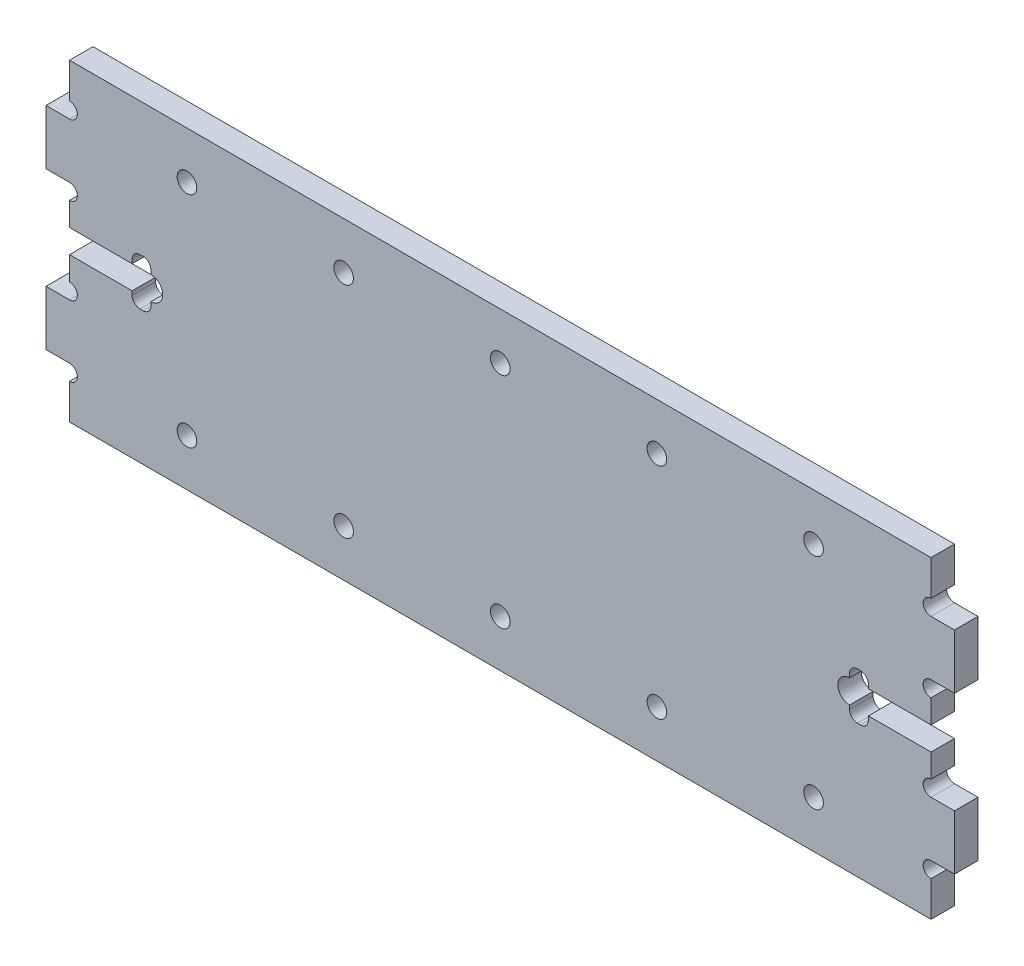
SolidWorks part; units mm, degrees
material "Acrylic (Medium-high impact)"
ref_plane "Front Plane" through (0, 0, 0) normal (0, 0, 1) x (1, 0, 0)
ref_plane "Top Plane" through (0, 0, 0) normal (0, 1, 0) x (1, 0, 0)
ref_plane "Right Plane" through (0, 0, 0) normal (1, 0, 0) x (0, 0, -1)
sketch "Sketch1" plane through (0, 0, 0) normal (0, 0, 1) x (1, 0, 0)
  line L0 (0, 20) -> (0, -20) construction
  line L1 (-55, 20) -> (55, 20)
  line L2 (-55, 20) -> (-55, -20)
  line L3 (-55, -20) -> (55, -20)
  line L4 (55, 20) -> (55, -20)
  line L5 (55, 0) -> (-55, 0) construction
  point P8 (0, 0)
extrude "Boss-Extrude1" add sketch "Sketch1" along normal blind 3
sketch "Sketch2" plane through (0, 0, 3) normal (0, 0, 1) x (1, 0, 0)
  line L0 (-55, 0) -> (55, 0) construction
  line L1 (-55, 20) -> (-55, -20) construction
  line L2 (55, -20) -> (55, 20) construction
  line L3 (55, 0) -> (55, -20) construction
  line L4 (55, 0) -> (55, 20) construction
  line L5 (55, 20) -> (58, 20) construction
  line L6 (58, 20) -> (58, -20) construction
  line L7 (58, -20) -> (55, -20) construction
  line L8 (0, 20) -> (0, -20) construction
  line L9 (55, 20) -> (-55, 20) construction
  line L10 (-55, -20) -> (55, -20) construction
  line L11 (55, -10) -> (58, -10) construction
  line L12 (55, 10) -> (58, 10) construction
  line L13 (58, 10) -> (58, 13.5)
  line L14 (58, 10) -> (58, 6.5)
  line L15 (58, 6.5) -> (55, 6.5)
  line L16 (55, 6.5) -> (55, 13.5)
  line L17 (55, 13.5) -> (58, 13.5)
  line L18 (55, -10) -> (55, -6.5)
  line L19 (55, -6.5) -> (58, -6.5)
  line L20 (58, -6.5) -> (58, -13.5)
  line L21 (58, -13.5) -> (55, -13.5)
  line L22 (55, -13.5) -> (55, -10)
  line L23 (-55, 6.5) -> (-55, 13.5)
  line L24 (-55, -13.5) -> (-55, -10)
  line L25 (-55, -10) -> (-55, -6.5)
  line L26 (-55, 10) -> (-58, 10) construction
  line L27 (-55, -10) -> (-58, -10) construction
  line L28 (-58, -20) -> (-55, -20) construction
  line L29 (-58, 20) -> (-58, -20) construction
  line L30 (-55, 20) -> (-58, 20) construction
  line L31 (-58, -13.5) -> (-55, -13.5)
  line L32 (-58, -6.5) -> (-58, -13.5)
  line L33 (-55, -6.5) -> (-58, -6.5)
  line L34 (-55, 13.5) -> (-58, 13.5)
  line L35 (-58, 6.5) -> (-55, 6.5)
  line L36 (-58, 10) -> (-58, 6.5)
  line L37 (-58, 10) -> (-58, 13.5)
extrude "Boss-Extrude2" add sketch "Sketch2" against normal blind 3
sketch "Sketch3" plane through (0, 0, 3) normal (0, 0, 1) x (1, 0, 0)
  line L0 (-55, 0) -> (55, 0) construction
  line L1 (-55, 6.5) -> (-55, -6.5) construction
  line L2 (55, -6.5) -> (55, 6.5) construction
  line L3 (-55, 13.5) -> (-55, 14.5) construction
  line L4 (-55, 20) -> (-55, 13.5) construction
  line L5 (-55, 14.5) -> (55, 14.5) construction
  line L6 (55, 13.5) -> (55, 20) construction
  line L7 (55, 14.5) -> (55, 5.5) construction
  line L8 (55, 5.5) -> (-55, 5.5) construction
  line L9 (-55, -6.5) -> (-55, -5.5) construction
  line L10 (-55, -5.5) -> (55, -5.5) construction
  line L11 (55, -5.5) -> (55, -14.5) construction
  line L12 (55, -20) -> (55, -13.5) construction
  line L13 (55, -14.5) -> (-55, -14.5) construction
  line L14 (-55, -13.5) -> (-55, -20) construction
  circle A1 centre (-55, 14.5) radius 1
  circle A2 centre (-55, 5.5) radius 1
  circle A3 centre (-55, -5.5) radius 1
  circle A4 centre (-55, -14.5) radius 1
  circle A5 centre (55, 14.5) radius 1
  circle A6 centre (55, 5.5) radius 1
  circle A7 centre (55, -5.5) radius 1
  circle A8 centre (55, -14.5) radius 1
extrude "Cut-Extrude1" cut sketch "Sketch3" against normal blind 3
sketch "Sketch4" plane through (0, 0, 3) normal (0, 0, 1) x (1, 0, 0)
  line L0 (-55, 0) -> (55, 0) construction
  line L1 (-55, 4.5) -> (-55, -4.5) construction
  line L2 (55, -4.5) -> (55, 4.5) construction
  line L3 (55, 0) -> (55, -1.5) construction
  line L4 (55, -1.5) -> (-55, -1.5) construction
  line L5 (-55, -1.5) -> (-55, 1.5) construction
  line L6 (-55, 1.5) -> (55, 1.5) construction
  line L7 (55, 1.5) -> (47, 1.5) construction
  line L8 (47, 20) -> (47, -20) construction
  line L9 (55, 20) -> (-55, 20) construction
  line L10 (-55, -20) -> (55, -20) construction
  line L11 (-55, 1.5) -> (-47, 1.5) construction
  line L12 (-47, 20) -> (-47, -20) construction
  line L13 (-47, 20) -> (-44.6, 20) construction
  line L14 (-44.6, 20) -> (-44.6, -20) construction
  line L15 (47, 20) -> (44.6, 20) construction
  line L16 (44.6, 20) -> (44.6, -20) construction
  line L17 (55, 1.5) -> (55, 3) construction
  line L18 (55, 3) -> (-55, 3) construction
  line L19 (-55, 3) -> (-55, -3) construction
  line L20 (-55, -3) -> (55, -3) construction
  line L21 (-44.6, 0) -> (-43.1, 0) construction
  line L22 (44.6, 0) -> (43.1, 0) construction
  line L24 (-55, 1.5) -> (-47, 1.5)
  line L25 (-55, 1.5) -> (-55, -1.5)
  line L26 (-55, -1.5) -> (-47, -1.5)
  line L27 (-47, 1.5) -> (-47, -1.5)
  line L28 (-47, 3) -> (-44.6, 3)
  line L29 (-47, 3) -> (-47, -3)
  line L30 (-47, -3) -> (-44.6, -3)
  line L31 (-44.6, 3) -> (-44.6, -3)
  line L32 (44.6, 3) -> (47, 3)
  line L33 (44.6, 3) -> (44.6, -3)
  line L34 (44.6, -3) -> (47, -3)
  line L35 (47, 3) -> (47, -3)
  line L36 (47, 1.5) -> (55, 1.5)
  line L37 (47, 1.5) -> (47, -1.5)
  line L38 (47, -1.5) -> (55, -1.5)
  line L39 (55, 1.5) -> (55, -1.5)
  arc A0 (44.6, 1.5) -> (44.6, -1.5) centre (44.6, 0) ccw
  arc A1 (-44.6, 1.5) -> (-44.6, -1.5) centre (-44.6, 0) cw
  line M10 (-55, 4.5) -> (-55, -4.5)
  line M24 (55, -4.5) -> (55, 4.5)
extrude "Cut-Extrude2" cut sketch "Sketch4" against normal blind 3 contours L27 L24 L26 M10 | L31 L28 L29 L27 L30 | A1 L31 | L35 L32 L33 L34 | L33 A0 | L35 L38 L36 M24
fillet "Fillet6" radius 1 8 edges at (-44.6, 3, 1.5) (-47, 3, 1.5) (-44.6, -3, 1.5) (-47, -3, 1.5) (47, 3, 1.5) (44.6, 3, 1.5) (47, -3, 1.5) (44.6, -3, 1.5)
sketch "Sketch6" plane through (0, 0, 3) normal (0, 0, 1) x (1, 0, 0)
  line L0 (0, 0) -> (0, 20) construction
  line L1 (55, 20) -> (-55, 20) construction
  line L2 (0, 20) -> (0, 14) construction
  line L3 (0, 0) -> (0, -20) construction
  line L4 (-55, -20) -> (55, -20) construction
  line L5 (0, -20) -> (0, -14) construction
  circle A0 centre (0, 14) radius 1.25
  circle A1 centre (0, -14) radius 1.25
  circle A2 centre (20, -14) radius 1.25
  circle A3 centre (20, 14) radius 1.25
  circle A4 centre (40, -14) radius 1.25
  circle A5 centre (40, 14) radius 1.25
  circle A6 centre (-20, -14) radius 1.25
  circle A7 centre (-20, 14) radius 1.25
  circle A8 centre (-40, -14) radius 1.25
  circle A9 centre (-40, 14) radius 1.25
  dimension "D1" = 3
  dimension "D2" = 3
extrude "Cut-Extrude4" cut sketch "Sketch6" against normal through all contours A8 | A6 | A1 | A2 | A4 | A5 | A3 | A0 | A7 | A9
